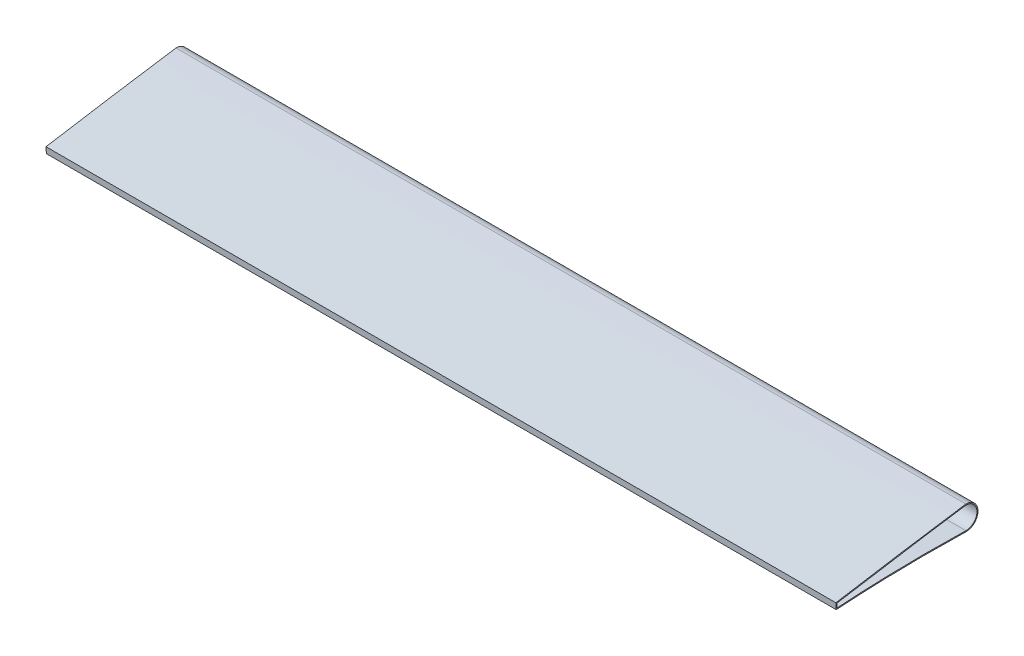
SolidWorks part; units mm, degrees
material "Zero density"
ref_plane "Piano frontale" through (0, 0, 0) normal (0, 0, 1) x (1, 0, 0)
ref_plane "Piano superiore" through (0, 0, 0) normal (0, 1, 0) x (1, 0, 0)
ref_plane "Piano destro" through (0, 0, 0) normal (1, 0, 0) x (0, 0, -1)
curve "Curva1"
  spline degree 3 poles (0, 0.1724, 248.285) (0, -0.053, 250.4273) (0, 0.2462, 248.3284) (0, 0.5529, 246.6445) (0, 1.2459, 242.6221) (0, 2.0989, 237.7464) (0, 3.1818, 231.3634) (0, 4.2933, 223.9772) (0, 5.7312, 215.5604) (0, 7.1315, 206.3004) (0, 8.6324, 196.1631) (0, 10.1162, 185.3524) (0, 11.5493, 173.9891) (0, 12.8816, 162.1914) (0, 14.0593, 150.0724) (0, 15.0523, 137.7438) (0, 15.8256, 125.3116) (0, 16.3834, 112.8888) (0, 16.7267, 100.597) (0, 16.8648, 88.5669) (0, 16.792, 76.9314) (0, 16.4941, 65.8165) (0, 15.9609, 55.3329) (0, 15.1594, 45.573) (0, 14.0978, 36.6074) (0, 12.7884, 28.4972) (0, 11.2839, 21.2988) (0, 9.6413, 15.0749) (0, 7.9136, 9.8809) (0, 6.1182, 5.7699) (0, 4.2384, 2.7289) (0, 2.3057, 0.8126) (0, 0.7927, 0.0312) (0, -0.4105, -0.0213) (0, -1.7115, 0.4949) (0, -2.8658, 2.6253) (0, -4.0404, 5.6977) (0, -4.9287, 10.0719) (0, -5.5974, 15.6262) (0, -6.0122, 22.4122) (0, -6.265, 30.3619) (0, -6.3814, 39.3972) (0, -6.3554, 49.3987) (0, -6.2185, 60.2453) (0, -5.9476, 71.8018) (0, -5.5368, 83.9408) (0, -4.9386, 96.5461) (0, -4.1527, 109.5201) (0, -3.2196, 122.7671) (0, -2.1909, 136.1764) (0, -1.148, 149.6158) (0, -0.1602, 162.9314) (0, 0.706, 175.9537) (0, 1.3896, 188.4999) (0, 1.8332, 200.3712) (0, 1.9676, 211.3376) (0, 1.8232, 221.1842) (0, 1.4973, 229.6804) (0, 1.0741, 236.8065) (0, 0.6857, 242.1894) (0, 0.3087, 246.5181) (0, 0.1724, 248.285) (0, -0.053, 250.4273) (0, 0.2462, 248.3284) knots -0.014202 -0.006329 -0.001589 0 0.001576 0.006211 0.01368 0.023764 0.036307 0.051658 0.068045 0.086769 0.107053 0.128647 0.151303 0.174786 0.19886 0.223309 0.247929 0.272522 0.296848 0.320648 0.343669 0.365658 0.3864 0.405741 0.423561 0.439779 0.454311 0.467034 0.477831 0.486643 0.493542 0.498786 0.50271 0.50309 0.505896 0.510322 0.516831 0.525521 0.536535 0.549945 0.565696 0.583577 0.603379 0.624844 0.647727 0.671743 0.696673 0.722357 0.748609 0.77521 0.801891 0.828329 0.854175 0.879074 0.902636 0.924421 0.943939 0.960827 0.974827 0.985798 0.993671 0.998411 1 1.001576 1.006211 1.01368 periodic
sketch "Schizzo1" plane through (0, 0, 0) normal (1, 0, 0) x (0, 0, -1)
  line L0 (-250, 0) -> (-249.9688, 0) construction
  line L3 (-200, 8.0593) -> (-200, 1.7757) construction
  arc A1 (-200, 8.0593) -> (-200, 1.7757) centre (-200, 4.9175) cw
  circle A2 centre (-200, 4.9175) radius 1.65
  spline S1 degree 3 poles (-200, 8.0593) (-202.1874, 7.7398) (-207.5057, 6.9493) (-215.5604, 5.7312) (-223.9772, 4.2933) (-231.3634, 3.1818) (-237.7464, 2.0989) (-242.6221, 1.2459) (-246.6445, 0.5529) (-248.3284, 0.2462) (-250.4273, -0.053) (-248.285, 0.1724) (-246.5181, 0.3087) (-242.1894, 0.6857) (-236.8065, 1.0741) (-229.6804, 1.4973) (-221.1842, 1.8232) (-211.3376, 1.9676) (-204.1306, 1.8793) (-200.2242, 1.7814) (-200, 1.7757) knots 0.900158 0.900158 0.900158 0.900158 0.913231 0.931955 0.948342 0.963693 0.976236 0.98632 0.993789 0.998424 1 1.001589 1.006329 1.014202 1.025173 1.039173 1.056061 1.075579 1.097364 1.09869 1.09869 1.09869 1.09869
  spline S2 degree 3 poles (-248.3284, 0.2462) (-250.4273, -0.053) (-248.285, 0.1724) (-246.5181, 0.3087) (-242.1894, 0.6857) (-236.8065, 1.0741) (-229.6804, 1.4973) (-221.1842, 1.8232) (-211.3376, 1.9676) (-200.3712, 1.8332) (-188.4999, 1.3896) (-175.9537, 0.706) (-162.9314, -0.1602) (-149.6158, -1.148) (-136.1764, -2.1909) (-122.7671, -3.2196) (-109.5201, -4.1527) (-96.5461, -4.9386) (-83.9408, -5.5368) (-71.8018, -5.9476) (-60.2453, -6.2185) (-49.3987, -6.3554) (-39.3972, -6.3814) (-30.3619, -6.265) (-22.4122, -6.0122) (-15.6262, -5.5974) (-10.0719, -4.9287) (-5.6977, -4.0404) (-2.6253, -2.8658) (-0.4949, -1.7115) (0.0213, -0.4105) (-0.0312, 0.7927) (-0.8126, 2.3057) (-2.7289, 4.2384) (-5.7699, 6.1182) (-9.8809, 7.9136) (-15.0749, 9.6413) (-21.2988, 11.2839) (-28.4972, 12.7884) (-36.6074, 14.0978) (-45.573, 15.1594) (-55.3329, 15.9609) (-65.8165, 16.4941) (-76.9314, 16.792) (-88.5669, 16.8648) (-100.597, 16.7267) (-112.8888, 16.3834) (-125.3116, 15.8256) (-137.7438, 15.0523) (-150.0724, 14.0593) (-162.1914, 12.8816) (-173.9891, 11.5493) (-185.3524, 10.1162) (-196.1631, 8.6324) (-206.3004, 7.1315) (-215.5604, 5.7312) (-223.9772, 4.2933) (-231.3634, 3.1818) (-237.7464, 2.0989) (-242.6221, 1.2459) (-246.6445, 0.5529) (-248.3284, 0.2462) (-250.4273, -0.053) (-248.285, 0.1724) knots -0.01368 -0.006211 -0.001576 0 0.001589 0.006329 0.014202 0.025173 0.039173 0.056061 0.075579 0.097364 0.120926 0.145825 0.171671 0.198109 0.22479 0.251391 0.277643 0.303327 0.328257 0.352273 0.375156 0.396621 0.416423 0.434304 0.450055 0.463465 0.474479 0.483169 0.489678 0.494104 0.49691 0.49729 0.501214 0.506458 0.513357 0.522169 0.532966 0.545689 0.560221 0.576439 0.594259 0.6136 0.634342 0.656331 0.679352 0.703152 0.727478 0.752071 0.776691 0.80114 0.825214 0.848697 0.871353 0.892947 0.913231 0.931955 0.948342 0.963693 0.976236 0.98632 0.993789 0.998424 1 1.001589 1.006329 1.014202 only from (-250, 0) to (-250, 0) construction
  spline S3 degree 3 poles (-248.3284, 0.2462) (-250.4273, -0.053) (-248.285, 0.1724) (-246.5181, 0.3087) (-242.1894, 0.6857) (-236.8065, 1.0741) (-229.6804, 1.4973) (-221.1842, 1.8232) (-211.3376, 1.9676) (-200.3712, 1.8332) (-188.4999, 1.3896) (-175.9537, 0.706) (-162.9314, -0.1602) (-149.6158, -1.148) (-136.1764, -2.1909) (-122.7671, -3.2196) (-109.5201, -4.1527) (-96.5461, -4.9386) (-83.9408, -5.5368) (-71.8018, -5.9476) (-60.2453, -6.2185) (-49.3987, -6.3554) (-39.3972, -6.3814) (-30.3619, -6.265) (-22.4122, -6.0122) (-15.6262, -5.5974) (-10.0719, -4.9287) (-5.6977, -4.0404) (-2.6253, -2.8658) (-0.4949, -1.7115) (0.0213, -0.4105) (-0.0312, 0.7927) (-0.8126, 2.3057) (-2.7289, 4.2384) (-5.7699, 6.1182) (-9.8809, 7.9136) (-15.0749, 9.6413) (-21.2988, 11.2839) (-28.4972, 12.7884) (-36.6074, 14.0978) (-45.573, 15.1594) (-55.3329, 15.9609) (-65.8165, 16.4941) (-76.9314, 16.792) (-88.5669, 16.8648) (-100.597, 16.7267) (-112.8888, 16.3834) (-125.3116, 15.8256) (-137.7438, 15.0523) (-150.0724, 14.0593) (-162.1914, 12.8816) (-173.9891, 11.5493) (-185.3524, 10.1162) (-196.1631, 8.6324) (-206.3004, 7.1315) (-215.5604, 5.7312) (-223.9772, 4.2933) (-231.3634, 3.1818) (-237.7464, 2.0989) (-242.6221, 1.2459) (-246.6445, 0.5529) (-248.3284, 0.2462) (-250.4273, -0.053) (-248.285, 0.1724) knots -0.01368 -0.006211 -0.001576 0 0.001589 0.006329 0.014202 0.025173 0.039173 0.056061 0.075579 0.097364 0.120926 0.145825 0.171671 0.198109 0.22479 0.251391 0.277643 0.303327 0.328257 0.352273 0.375156 0.396621 0.416423 0.434304 0.450055 0.463465 0.474479 0.483169 0.489678 0.494104 0.49691 0.49729 0.501214 0.506458 0.513357 0.522169 0.532966 0.545689 0.560221 0.576439 0.594259 0.6136 0.634342 0.656331 0.679352 0.703152 0.727478 0.752071 0.776691 0.80114 0.825214 0.848697 0.871353 0.892947 0.913231 0.931955 0.948342 0.963693 0.976236 0.98632 0.993789 0.998424 1 1.001589 1.006329 1.014202 only from (-250, 0) to (-250, 0) construction
  dimension "D2" = 3.3
  dimension "D1" = 6.2836
  dimension "D7" = 50
extrude "CorpoFoam" add sketch "Schizzo1" along normal blind 225
ref_plane "PianoAusiliario" through (-15, 0, 0) normal (-1, 0, 0) x (0, 0, 1)
sketch "Schizzo4" plane through (-15, 0, 0) normal (-1, 0, 0) x (0, 0, 1)
  circle A0 centre (200, 4.9175) radius 1.65 construction
  circle A1 centre (200, 4.9175) radius 1.65
  arc A3 (200, 8.0593) -> (200, 1.7757) centre (200, 4.9175) ccw
  arc A5 (200, 8.0593) -> (200, 1.7757) centre (200, 4.9175) ccw
  spline S2 degree 3 poles (-275.5956, 1910.9332) (-192.3565, -135.6254) (6.7635, -0.5396) (211.3376, 1.9676) (221.1842, 1.8232) (229.6804, 1.4973) (236.8065, 1.0741) (242.1894, 0.6857) (246.5181, 0.3087) (248.285, 0.1724) (250.4273, -0.053) (248.3284, 0.2462) (246.6445, 0.5529) (242.6221, 1.2459) (237.7464, 2.0989) (231.3634, 3.1818) (223.9772, 4.2933) (215.5604, 5.7312) (27.3941, 34.1859) (-161.6085, 46.0507) (-539.4356, -1822.7054) knots -0.267254 -0.267254 -0.267254 -0.267254 0.901484 0.923269 0.942787 0.959674 0.973675 0.984645 0.992518 0.997259 0.998847 1.000423 1.005059 1.012527 1.022612 1.035154 1.050505 1.066892 1.085617 2.176153 2.176153 2.176153 2.176153 only from (200, 1.7757) to (200, 8.0593)
  spline S4 degree 3 poles (200, 1.7757) (200.2242, 1.7814) (204.1306, 1.8793) (211.3376, 1.9676) (221.1842, 1.8232) (229.6804, 1.4973) (236.8065, 1.0741) (242.1894, 0.6857) (246.5181, 0.3087) (248.285, 0.1724) (250.4273, -0.053) (248.3284, 0.2462) (246.6445, 0.5529) (242.6221, 1.2459) (237.7464, 2.0989) (231.3634, 3.1818) (223.9772, 4.2933) (215.5604, 5.7312) (207.5057, 6.9493) (202.1874, 7.7398) (200, 8.0593) knots 0.900158 0.900158 0.900158 0.900158 0.901484 0.923269 0.942787 0.959674 0.973675 0.984645 0.992518 0.997259 0.998847 1.000423 1.005059 1.012527 1.022612 1.035154 1.050505 1.066892 1.085617 1.09869 1.09869 1.09869 1.09869
  dimension "D1" = 0
extrude "CorpoCentina" add sketch "Schizzo4" along normal blind 5 separate body
sketch "Schizzo6" plane through (0, 0, 0) normal (-1, 0, 0) x (0, 0, 1)
  arc A3 (200, 8.0593) -> (200, 1.7757) centre (200, 4.9175) ccw
  arc A5 (200, 8.0593) -> (200, 1.7757) centre (200, 4.9175) ccw
  spline S2 degree 3 poles (-303.7555, 2910.4824) (-247.3154, -175.4676) (-21.0339, -0.8803) (211.3376, 1.9676) (221.1842, 1.8232) (229.6804, 1.4973) (236.8065, 1.0741) (242.1894, 0.6857) (246.5181, 0.3087) (248.285, 0.1724) (250.4273, -0.053) (248.3284, 0.2462) (246.6445, 0.5529) (242.6221, 1.2459) (237.7464, 2.0989) (231.3634, 3.1818) (223.9772, 4.2933) (215.5604, 5.7312) (-0.1576, 38.3523) (-217.8533, 49.2195) (-724.5548, -2805.3121) knots -0.431674 -0.431674 -0.431674 -0.431674 0.901484 0.923269 0.942787 0.959674 0.973675 0.984645 0.992518 0.997259 0.998847 1.000423 1.005059 1.012527 1.022612 1.035154 1.050505 1.066892 1.085617 2.340973 2.340973 2.340973 2.340973 only from (200, 1.7757) to (200, 8.0593)
  spline S4 degree 3 poles (200, 1.7757) (200.2242, 1.7814) (204.1306, 1.8793) (211.3376, 1.9676) (221.1842, 1.8232) (229.6804, 1.4973) (236.8065, 1.0741) (242.1894, 0.6857) (246.5181, 0.3087) (248.285, 0.1724) (250.4273, -0.053) (248.3284, 0.2462) (246.6445, 0.5529) (242.6221, 1.2459) (237.7464, 2.0989) (231.3634, 3.1818) (223.9772, 4.2933) (215.5604, 5.7312) (207.5057, 6.9493) (202.1874, 7.7398) (200, 8.0593) knots 0.900158 0.900158 0.900158 0.900158 0.901484 0.923269 0.942787 0.959674 0.973675 0.984645 0.992518 0.997259 0.998847 1.000423 1.005059 1.012527 1.022612 1.035154 1.050505 1.066892 1.085617 1.09869 1.09869 1.09869 1.09869
  dimension "D1" = 0
extrude "RimozioneFoam" cut sketch "Schizzo6" against normal through all
sketch "Schizzo7" plane through (-20, 0, 0) normal (-1, 0, 0) x (0, 0, 1)
  line L0 (228.544, 2.7244) -> (228.4772, 1.5262) construction
  line L1 (228.4772, 1.5262) -> (236.6645, 1.07) construction
  line L2 (236.6645, 1.07) -> (236.7313, 2.2681) construction
  line L3 (236.7313, 2.2681) -> (228.544, 2.7244) construction
  line L4 (238.0297, 25.5691) -> (235.3675, -22.2062)
  line L5 (235.3675, -22.2062) -> (291.7834, -25.3498)
  line L6 (291.7834, -25.3498) -> (294.4455, 22.4255)
  line L7 (294.4455, 22.4255) -> (238.0297, 25.5691)
  spline S0 degree 3 poles (248.285, 0.1724) (250.4273, -0.053) (248.3284, 0.2462) (246.6445, 0.5529) (242.6221, 1.2459) (237.7464, 2.0989) (231.3634, 3.1818) (223.9772, 4.2933) (215.5604, 5.7312) (206.3004, 7.1315) (196.1631, 8.6324) (185.3524, 10.1162) (173.9891, 11.5493) (162.1914, 12.8816) (150.0724, 14.0593) (137.7438, 15.0523) (125.3116, 15.8256) (112.8888, 16.3834) (100.597, 16.7267) (88.5669, 16.8648) (76.9314, 16.792) (65.8165, 16.4941) (55.3329, 15.9609) (45.573, 15.1594) (36.6074, 14.0978) (28.4972, 12.7884) (21.2988, 11.2839) (15.0749, 9.6413) (9.8809, 7.9136) (5.7699, 6.1182) (2.7289, 4.2384) (0.8126, 2.3057) (0.0312, 0.7927) (-0.0213, -0.4105) (0.4949, -1.7115) (2.6253, -2.8658) (5.6977, -4.0404) (10.0719, -4.9287) (15.6262, -5.5974) (22.4122, -6.0122) (30.3619, -6.265) (39.3972, -6.3814) (49.3987, -6.3554) (60.2453, -6.2185) (71.8018, -5.9476) (83.9408, -5.5368) (96.5461, -4.9386) (109.5201, -4.1527) (122.7671, -3.2196) (136.1764, -2.1909) (149.6158, -1.148) (162.9314, -0.1602) (175.9537, 0.706) (188.4999, 1.3896) (200.3712, 1.8332) (211.3376, 1.9676) (221.1842, 1.8232) (229.6804, 1.4973) (236.8065, 1.0741) (242.1894, 0.6857) (246.5181, 0.3087) (248.285, 0.1724) (250.4273, -0.053) (248.3284, 0.2462) knots -0.014202 -0.006329 -0.001589 0 0.001576 0.006211 0.01368 0.023764 0.036307 0.051658 0.068045 0.086769 0.107053 0.128647 0.151303 0.174786 0.19886 0.223309 0.247929 0.272522 0.296848 0.320648 0.343669 0.365658 0.3864 0.405741 0.423561 0.439779 0.454311 0.467034 0.477831 0.486643 0.493542 0.498786 0.50271 0.50309 0.505896 0.510322 0.516831 0.525521 0.536535 0.549945 0.565696 0.583577 0.603379 0.624844 0.647727 0.671743 0.696673 0.722357 0.748609 0.77521 0.801891 0.828329 0.854175 0.879074 0.902636 0.924421 0.943939 0.960827 0.974827 0.985798 0.993671 0.998411 1 1.001576 1.006211 1.01368 only from (250, 0) to (250, 0) construction
  spline S1 degree 3 poles (248.285, 0.1724) (250.4273, -0.053) (248.3284, 0.2462) (246.6445, 0.5529) (242.6221, 1.2459) (237.7464, 2.0989) (231.3634, 3.1818) (223.9772, 4.2933) (215.5604, 5.7312) (206.3004, 7.1315) (196.1631, 8.6324) (185.3524, 10.1162) (173.9891, 11.5493) (162.1914, 12.8816) (150.0724, 14.0593) (137.7438, 15.0523) (125.3116, 15.8256) (112.8888, 16.3834) (100.597, 16.7267) (88.5669, 16.8648) (76.9314, 16.792) (65.8165, 16.4941) (55.3329, 15.9609) (45.573, 15.1594) (36.6074, 14.0978) (28.4972, 12.7884) (21.2988, 11.2839) (15.0749, 9.6413) (9.8809, 7.9136) (5.7699, 6.1182) (2.7289, 4.2384) (0.8126, 2.3057) (0.0312, 0.7927) (-0.0213, -0.4105) (0.4949, -1.7115) (2.6253, -2.8658) (5.6977, -4.0404) (10.0719, -4.9287) (15.6262, -5.5974) (22.4122, -6.0122) (30.3619, -6.265) (39.3972, -6.3814) (49.3987, -6.3554) (60.2453, -6.2185) (71.8018, -5.9476) (83.9408, -5.5368) (96.5461, -4.9386) (109.5201, -4.1527) (122.7671, -3.2196) (136.1764, -2.1909) (149.6158, -1.148) (162.9314, -0.1602) (175.9537, 0.706) (188.4999, 1.3896) (200.3712, 1.8332) (211.3376, 1.9676) (221.1842, 1.8232) (229.6804, 1.4973) (236.8065, 1.0741) (242.1894, 0.6857) (246.5181, 0.3087) (248.285, 0.1724) (250.4273, -0.053) (248.3284, 0.2462) knots -0.014202 -0.006329 -0.001589 0 0.001576 0.006211 0.01368 0.023764 0.036307 0.051658 0.068045 0.086769 0.107053 0.128647 0.151303 0.174786 0.19886 0.223309 0.247929 0.272522 0.296848 0.320648 0.343669 0.365658 0.3864 0.405741 0.423561 0.439779 0.454311 0.467034 0.477831 0.486643 0.493542 0.498786 0.50271 0.50309 0.505896 0.510322 0.516831 0.525521 0.536535 0.549945 0.565696 0.583577 0.603379 0.624844 0.647727 0.671743 0.696673 0.722357 0.748609 0.77521 0.801891 0.828329 0.854175 0.879074 0.902636 0.924421 0.943939 0.960827 0.974827 0.985798 0.993671 0.998411 1 1.001576 1.006211 1.01368 only from (250, 0) to (250, 0) construction
  spline S2 degree 3 poles (200, 1.7757) (200.2242, 1.7814) (204.1306, 1.8793) (211.3376, 1.9676) (221.1842, 1.8232) (229.6804, 1.4973) (236.8065, 1.0741) (242.1894, 0.6857) (246.5181, 0.3087) (248.285, 0.1724) (250.4273, -0.053) (248.3284, 0.2462) (246.6445, 0.5529) (242.6221, 1.2459) (237.7464, 2.0989) (231.3634, 3.1818) (223.9772, 4.2933) (215.5604, 5.7312) (207.5057, 6.9493) (202.1874, 7.7398) (200, 8.0593) knots 0.900158 0.900158 0.900158 0.900158 0.901484 0.923269 0.942787 0.959674 0.973675 0.984645 0.992518 0.997259 0.998847 1.000423 1.005059 1.012527 1.022612 1.035154 1.050505 1.066892 1.085617 1.09869 1.09869 1.09869 1.09869 construction
  dimension "D1" = 1.2
  dimension "D2" = 8.2
  dimension "D3" = 47.7753
  dimension "D4" = 56.4158
  dimension "D5" = 22.8447
extrude "IntaglioPosteriore" cut sketch "Schizzo7" against normal through all
sketch "Schizzo8" plane through (-20, 0, 0) normal (-1, 0, 0) x (0, 0, 1)
  line L0 (236.9472, 0.7509) -> (237.0457, 2.5187)
  line L1 (236.6645, 1.07) -> (236.7313, 2.2681)
  line L2 (236.6645, 1.07) -> (236.7313, 2.2681)
  arc A0 (200.0223, 8.3592) -> (200.004, 1.4757) centre (200, 4.9175) ccw
  arc A1 (200, 8.0593) -> (200, 1.7757) centre (200, 4.9175) ccw
  arc A2 (200, 8.0593) -> (200, 1.7757) centre (200, 4.9175) ccw
  spline S0 degree 1 poles (237.0457, 2.5187) (200.0223, 8.3592) knots 0 0 1 1 construction
  spline S1 degree 1 poles (200.004, 1.4757) (236.9472, 0.7509) knots 0 0 1 1 construction
  spline S2 degree 3 poles (-2540.3946, 1136.515) (409.2648, -53.8181) (312.0502, -8.96) (223.9772, 4.2933) (215.5604, 5.7312) (-0.1582, 38.3524) (-217.8546, 49.2195) (-724.5594, -2805.338) knots 0.538896 0.538896 0.538896 0.538896 1.035154 1.050505 1.066892 1.085617 2.340977 2.340977 2.340977 2.340977 only from (236.7313, 2.2681) to (200, 8.0593)
  spline S3 degree 3 poles (-303.7565, 2910.5388) (-247.3181, -175.4697) (-21.0353, -0.8803) (211.3376, 1.9676) (221.1842, 1.8232) (316.6081, -1.8371) (425.0689, -40.6316) (-2734.8403, 412.4156) knots -0.431682 -0.431682 -0.431682 -0.431682 0.901484 0.923269 0.942787 0.959674 1.489396 1.489396 1.489396 1.489396 only from (200, 1.7757) to (236.6645, 1.07)
  spline S4 degree 3 poles (236.7313, 2.2681) (235.1128, 2.5448) (230.8974, 3.2519) (223.9772, 4.2933) (215.5604, 5.7312) (207.5057, 6.9493) (202.1874, 7.7398) (200, 8.0593) knots 1.025405 1.025405 1.025405 1.025405 1.035154 1.050505 1.066892 1.085617 1.09869 1.09869 1.09869 1.09869
  spline S5 degree 3 poles (200, 1.7757) (200.2242, 1.7814) (204.1306, 1.8793) (211.3376, 1.9676) (221.1842, 1.8232) (229.4758, 1.5052) (234.5257, 1.2094) (236.6645, 1.07) knots 0.900158 0.900158 0.900158 0.900158 0.901484 0.923269 0.942787 0.959674 0.972461 0.972461 0.972461 0.972461
  spline S6 degree 3 poles (237.0457, 2.5187) (233.9624, 3.0459) (229.3181, 3.7886) (223.165, 4.7455) (217.006, 5.7838) (209.2884, 6.9944) (203.112, 7.9079) (200.0223, 8.3592) knots 1.024875 1.024875 1.024875 1.024875 1.04334 1.052572 1.061804 1.080268 1.098732 1.098732 1.098732 1.098732
  spline S7 degree 3 poles (200.004, 1.4757) (203.0829, 1.555) (209.2398, 1.6529) (218.4924, 1.5843) (226.1617, 1.3461) (232.348, 1.0396) (235.4122, 0.851) (236.9472, 0.7509) knots 0.90015 0.90015 0.90015 0.90015 0.918378 0.936607 0.954835 0.963949 0.973063 0.973063 0.973063 0.973063
  dimension "D1" = 0
  dimension "D2" = 0.3
extrude "Rivestimento" add sketch "Schizzo8" along normal blind 225 separate body
sketch "Schizzo9" plane through (-15, 0, 0) normal (1, 0, 0) x (0, 0, -1)
  line L1 (-236.7313, 2.2681) -> (-236.6645, 1.07)
  line L2 (-236.7313, 2.2681) -> (-236.6645, 1.07)
  arc A1 (-200, 1.7757) -> (-200, 8.0593) centre (-200, 4.9175) ccw
  arc A2 (-200, 1.7757) -> (-200, 8.0593) centre (-200, 4.9175) ccw
  spline S2 degree 3 poles (892.3011, -3791.1849) (262.4806, 51.2211) (21.9635, 41.6498) (-215.5604, 5.7312) (-223.9772, 4.2933) (-319.9257, -10.1451) (-427.3086, -62.3702) (3467.5617, 1510.8477) knots -0.347325 -0.347325 -0.347325 -0.347325 1.038479 1.057203 1.07359 1.088941 1.632413 1.632413 1.632413 1.632413 only from (-200, 8.0593) to (-236.7313, 2.2681)
  spline S3 degree 3 poles (3724.4113, 554.9468) (-445.1369, -48.0579) (-325.0731, -2.1618) (-221.1842, 1.8232) (-211.3376, 1.9676) (43.0335, -1.15) (290.7528, -210.586) (315.3799, 3910.4108) knots 0.333002 0.333002 0.333002 0.333002 0.912945 0.929832 0.94935 0.971135 2.434418 2.434418 2.434418 2.434418 only from (-236.6645, 1.07) to (-200, 1.7757)
  spline S4 degree 3 poles (-200, 8.0593) (-202.1874, 7.7398) (-207.5057, 6.9493) (-215.5604, 5.7312) (-223.9772, 4.2933) (-230.8974, 3.2519) (-235.1128, 2.5448) (-236.7313, 2.2681) knots 1.025405 1.025405 1.025405 1.025405 1.038479 1.057203 1.07359 1.088941 1.09869 1.09869 1.09869 1.09869
  spline S5 degree 3 poles (-236.6645, 1.07) (-234.5257, 1.2094) (-229.4758, 1.5052) (-221.1842, 1.8232) (-211.3376, 1.9676) (-204.1306, 1.8793) (-200.2242, 1.7814) (-200, 1.7757) knots 0.900158 0.900158 0.900158 0.900158 0.912945 0.929832 0.94935 0.971135 0.972461 0.972461 0.972461 0.972461
  dimension "D1" = 0
extrude "RimozioneCentina" cut sketch "Schizzo9" against normal through all
